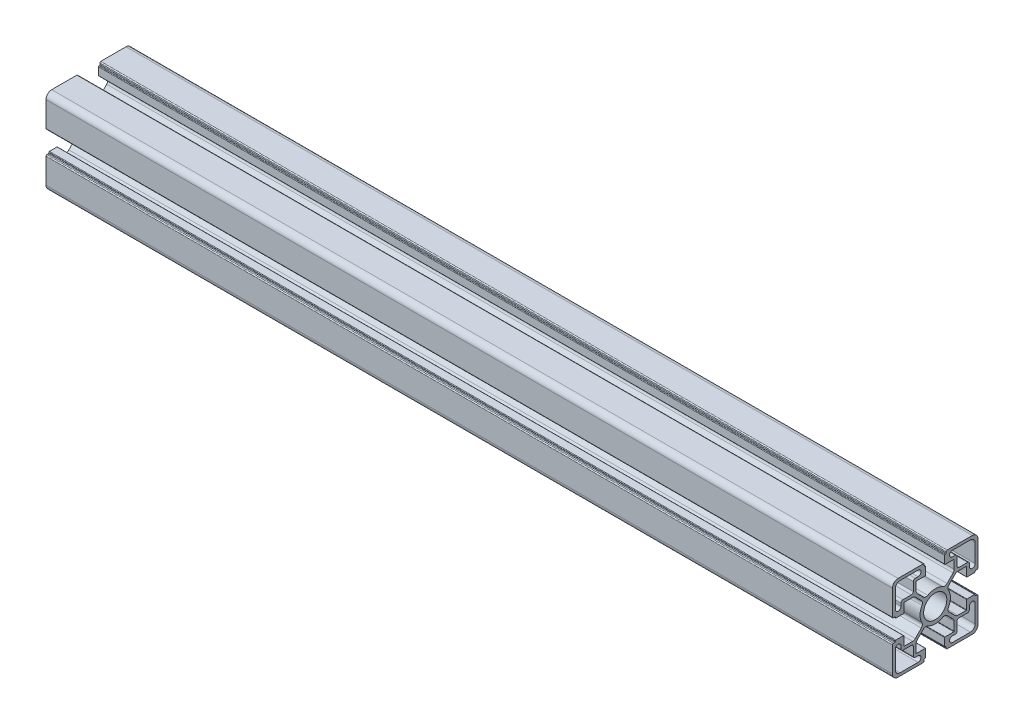
SolidWorks part; units mm, degrees
material "Alliage 6061"
ref_plane "Plan de face" through (0, 0, 0) normal (0, 0, 1) x (1, 0, 0)
ref_plane "Plan de dessus" through (0, 0, 0) normal (0, 1, 0) x (1, 0, 0)
ref_plane "Plan de droite" through (0, 0, 0) normal (1, 0, 0) x (0, 0, -1)
sketch "Esquisse1" plane through (0, 0, 0) normal (1, 0, 0) x (0, 0, -1)
  line L0 (0, 0) -> (-37.5261, 37.5261) construction
  line L1 (0, 0) -> (-46.9556, 0) construction
  line L2 (-22.5, 19.5) -> (-22.5, 6.3)
  line L3 (-20.7, 5) -> (-16.7, 5)
  line L4 (-16.5, 5.2) -> (-16.5, 9.8)
  line L5 (-16.3, 10) -> (-11.8642, 10)
  line L6 (-10.4924, 9.4318) -> (-7.2967, 6.236)
  line L7 (-21, 18.5) -> (-21, 9)
  line L8 (-16.5, 5) -> (-16.5, 10) construction
  line L9 (-18, 9) -> (-18, 10.5)
  line L10 (-17, 11.5) -> (-12.5, 11.5)
  line L11 (-22, 5.8) -> (-21.3, 5.8)
  line L12 (-21, 5.5) -> (-21, 5.3)
  line L13 (-21, 22.5) -> (-21, 6.5) construction
  line L14 (-18, 11.5) -> (-10.4393, 11.5) construction
  line L15 (-10.4393, 11.5) -> (-5.1016, 6.1623) construction
  line L16 (-18, 6.5) -> (-18, 11.5) construction
  line L17 (-22.5, 22.5) -> (-22.5, 5) construction
  line L18 (-22.5, 5) -> (-16.5, 5) construction
  line L19 (-21, 6.5) -> (-18, 6.5) construction
  line L20 (-16.5, 10) -> (-11.0607, 10) construction
  line L21 (-11.0607, 10) -> (-6.1623, 5.1016) construction
  line L22 (-5.5, 21) -> (-5.3, 21)
  line L23 (-5.8, 22) -> (-5.8, 21.3)
  line L24 (-11.5, 17) -> (-11.5, 12.5)
  line L25 (-9, 18) -> (-10.5, 18)
  line L26 (-18.5, 21) -> (-9, 21)
  line L27 (-9.4318, 10.4924) -> (-6.236, 7.2967)
  line L28 (-10, 16.3) -> (-10, 11.8642)
  line L29 (-5.2, 16.5) -> (-9.8, 16.5)
  line L30 (-5, 20.7) -> (-5, 16.7)
  line L31 (-19.5, 22.5) -> (-6.3, 22.5)
  line L32 (19.5, 22.5) -> (6.3, 22.5)
  line L33 (5, 20.7) -> (5, 16.7)
  line L34 (5.2, 16.5) -> (9.8, 16.5)
  line L35 (10, 16.3) -> (10, 11.8642)
  line L36 (9.4318, 10.4924) -> (6.236, 7.2967)
  line L37 (18.5, 21) -> (9, 21)
  line L38 (9, 18) -> (10.5, 18)
  line L39 (11.5, 17) -> (11.5, 12.5)
  line L40 (5.8, 22) -> (5.8, 21.3)
  line L41 (5.5, 21) -> (5.3, 21)
  line L42 (21, 5.5) -> (21, 5.3)
  line L43 (22, 5.8) -> (21.3, 5.8)
  line L44 (17, 11.5) -> (12.5, 11.5)
  line L45 (18, 9) -> (18, 10.5)
  line L46 (21, 18.5) -> (21, 9)
  line L47 (10.4924, 9.4318) -> (7.2967, 6.236)
  line L48 (16.3, 10) -> (11.8642, 10)
  line L49 (16.5, 5.2) -> (16.5, 9.8)
  line L50 (20.7, 5) -> (16.7, 5)
  line L51 (22.5, 19.5) -> (22.5, 6.3)
  line L52 (0, 0) -> (37.5261, 37.5261) construction
  line L53 (0, 0) -> (0, 46.9556) construction
  line L54 (22.5, -19.5) -> (22.5, -6.3)
  line L55 (20.7, -5) -> (16.7, -5)
  line L56 (16.5, -5.2) -> (16.5, -9.8)
  line L57 (16.3, -10) -> (11.8642, -10)
  line L58 (10.4924, -9.4318) -> (7.2967, -6.236)
  line L59 (21, -18.5) -> (21, -9)
  line L60 (18, -9) -> (18, -10.5)
  line L61 (17, -11.5) -> (12.5, -11.5)
  line L62 (22, -5.8) -> (21.3, -5.8)
  line L63 (21, -5.5) -> (21, -5.3)
  line L64 (5.5, -21) -> (5.3, -21)
  line L65 (5.8, -22) -> (5.8, -21.3)
  line L66 (11.5, -17) -> (11.5, -12.5)
  line L67 (9, -18) -> (10.5, -18)
  line L68 (18.5, -21) -> (9, -21)
  line L69 (9.4318, -10.4924) -> (6.236, -7.2967)
  line L70 (10, -16.3) -> (10, -11.8642)
  line L71 (5.2, -16.5) -> (9.8, -16.5)
  line L72 (5, -20.7) -> (5, -16.7)
  line L73 (19.5, -22.5) -> (6.3, -22.5)
  line L74 (0, 0) -> (37.5261, -37.5261) construction
  line L75 (0, 0) -> (46.9556, 0) construction
  line L76 (-19.5, -22.5) -> (-6.3, -22.5)
  line L77 (-5, -20.7) -> (-5, -16.7)
  line L78 (-5.2, -16.5) -> (-9.8, -16.5)
  line L79 (-10, -16.3) -> (-10, -11.8642)
  line L80 (-9.4318, -10.4924) -> (-6.236, -7.2967)
  line L81 (-18.5, -21) -> (-9, -21)
  line L82 (-9, -18) -> (-10.5, -18)
  line L83 (-11.5, -17) -> (-11.5, -12.5)
  line L84 (-5.8, -22) -> (-5.8, -21.3)
  line L85 (-5.5, -21) -> (-5.3, -21)
  line L86 (-21, -5.5) -> (-21, -5.3)
  line L87 (-22, -5.8) -> (-21.3, -5.8)
  line L88 (-17, -11.5) -> (-12.5, -11.5)
  line L89 (-18, -9) -> (-18, -10.5)
  line L90 (-21, -18.5) -> (-21, -9)
  line L91 (-10.4924, -9.4318) -> (-7.2967, -6.236)
  line L92 (-16.3, -10) -> (-11.8642, -10)
  line L93 (-16.5, -5.2) -> (-16.5, -9.8)
  line L94 (-20.7, -5) -> (-16.7, -5)
  line L95 (-22.5, -19.5) -> (-22.5, -6.3)
  line L96 (0, 0) -> (-37.5261, -37.5261) construction
  line L97 (0, 0) -> (0, -46.9556) construction
  arc A0 (0, 6.1) -> (-6.1, 0) centre (0, 0) ccw
  arc A1 (-6.9766, 3.9149) -> (-8, 0) centre (0, 0) ccw
  arc A2 (-21, 9) -> (-18, 9) centre (-19.5, 9) ccw
  arc A3 (-22, 5.8) -> (-22.5, 6.3) centre (-22, 6.3) cw
  arc A4 (-21, 5.3) -> (-20.7, 5) centre (-20.7, 5.3) ccw
  arc A5 (-21.3, 5.8) -> (-21, 5.5) centre (-21.3, 5.5) cw
  arc A6 (-16.5, 9.8) -> (-16.3, 10) centre (-16.3, 9.8) cw
  arc A7 (-16.7, 5) -> (-16.5, 5.2) centre (-16.7, 5.2) ccw
  arc A8 (-7.2967, 6.236) -> (-6.9766, 3.9149) centre (-8.6685, 4.8643) cw
  arc A9 (-11.8642, 10) -> (-10.4924, 9.4318) centre (-11.8642, 8.06) cw
  arc A10 (-18, 10.5) -> (-17, 11.5) centre (-17, 10.5) cw
  arc A11 (-10.5, 18) -> (-11.5, 17) centre (-10.5, 17) ccw
  arc A12 (-10, 11.8642) -> (-9.4318, 10.4924) centre (-8.06, 11.8642) ccw
  arc A13 (-6.236, 7.2967) -> (-3.9149, 6.9766) centre (-4.8643, 8.6685) ccw
  arc A14 (-5, 16.7) -> (-5.2, 16.5) centre (-5.2, 16.7) cw
  arc A15 (-9.8, 16.5) -> (-10, 16.3) centre (-9.8, 16.3) ccw
  arc A16 (-5.8, 21.3) -> (-5.5, 21) centre (-5.5, 21.3) ccw
  arc A17 (-5.3, 21) -> (-5, 20.7) centre (-5.3, 20.7) cw
  arc A18 (-5.8, 22) -> (-6.3, 22.5) centre (-6.3, 22) ccw
  arc A19 (-9, 21) -> (-9, 18) centre (-9, 19.5) cw
  arc A20 (-3.9149, 6.9766) -> (0, 8) centre (0, 0) cw
  arc A21 (-12.5, 11.5) -> (-11.5, 12.5) centre (-12.5, 12.5) ccw
  arc A22 (-21, 18.5) -> (-18.5, 21) centre (-18.5, 18.5) cw
  arc A23 (-22.5, 19.5) -> (-19.5, 22.5) centre (-19.5, 19.5) cw
  arc A24 (6.1, 0) -> (0, 6.1) centre (0, 0) ccw
  arc A25 (3.9149, 6.9766) -> (0, 8) centre (0, 0) ccw
  arc A26 (9, 21) -> (9, 18) centre (9, 19.5) ccw
  arc A27 (5.8, 22) -> (6.3, 22.5) centre (6.3, 22) cw
  arc A28 (5.3, 21) -> (5, 20.7) centre (5.3, 20.7) ccw
  arc A29 (5.8, 21.3) -> (5.5, 21) centre (5.5, 21.3) cw
  arc A30 (9.8, 16.5) -> (10, 16.3) centre (9.8, 16.3) cw
  arc A31 (5, 16.7) -> (5.2, 16.5) centre (5.2, 16.7) ccw
  arc A32 (6.236, 7.2967) -> (3.9149, 6.9766) centre (4.8643, 8.6685) cw
  arc A33 (10, 11.8642) -> (9.4318, 10.4924) centre (8.06, 11.8642) cw
  arc A34 (10.5, 18) -> (11.5, 17) centre (10.5, 17) cw
  arc A35 (18, 10.5) -> (17, 11.5) centre (17, 10.5) ccw
  arc A36 (11.8642, 10) -> (10.4924, 9.4318) centre (11.8642, 8.06) ccw
  arc A37 (7.2967, 6.236) -> (6.9766, 3.9149) centre (8.6685, 4.8643) ccw
  arc A38 (16.7, 5) -> (16.5, 5.2) centre (16.7, 5.2) cw
  arc A39 (16.5, 9.8) -> (16.3, 10) centre (16.3, 9.8) ccw
  arc A40 (21.3, 5.8) -> (21, 5.5) centre (21.3, 5.5) ccw
  arc A41 (21, 5.3) -> (20.7, 5) centre (20.7, 5.3) cw
  arc A42 (22, 5.8) -> (22.5, 6.3) centre (22, 6.3) ccw
  arc A43 (21, 9) -> (18, 9) centre (19.5, 9) cw
  arc A44 (6.9766, 3.9149) -> (8, 0) centre (0, 0) cw
  arc A45 (11.5, 12.5) -> (12.5, 11.5) centre (12.5, 12.5) ccw
  arc A46 (18.5, 21) -> (21, 18.5) centre (18.5, 18.5) cw
  arc A47 (19.5, 22.5) -> (22.5, 19.5) centre (19.5, 19.5) cw
  arc A48 (0, -6.1) -> (6.1, 0) centre (0, 0) ccw
  arc A49 (6.9766, -3.9149) -> (8, 0) centre (0, 0) ccw
  arc A50 (21, -9) -> (18, -9) centre (19.5, -9) ccw
  arc A51 (22, -5.8) -> (22.5, -6.3) centre (22, -6.3) cw
  arc A52 (21, -5.3) -> (20.7, -5) centre (20.7, -5.3) ccw
  arc A53 (21.3, -5.8) -> (21, -5.5) centre (21.3, -5.5) cw
  arc A54 (16.5, -9.8) -> (16.3, -10) centre (16.3, -9.8) cw
  arc A55 (16.7, -5) -> (16.5, -5.2) centre (16.7, -5.2) ccw
  arc A56 (7.2967, -6.236) -> (6.9766, -3.9149) centre (8.6685, -4.8643) cw
  arc A57 (11.8642, -10) -> (10.4924, -9.4318) centre (11.8642, -8.06) cw
  arc A58 (18, -10.5) -> (17, -11.5) centre (17, -10.5) cw
  arc A59 (10.5, -18) -> (11.5, -17) centre (10.5, -17) ccw
  arc A60 (10, -11.8642) -> (9.4318, -10.4924) centre (8.06, -11.8642) ccw
  arc A61 (6.236, -7.2967) -> (3.9149, -6.9766) centre (4.8643, -8.6685) ccw
  arc A62 (5, -16.7) -> (5.2, -16.5) centre (5.2, -16.7) cw
  arc A63 (9.8, -16.5) -> (10, -16.3) centre (9.8, -16.3) ccw
  arc A64 (5.8, -21.3) -> (5.5, -21) centre (5.5, -21.3) ccw
  arc A65 (5.3, -21) -> (5, -20.7) centre (5.3, -20.7) cw
  arc A66 (5.8, -22) -> (6.3, -22.5) centre (6.3, -22) ccw
  arc A67 (9, -21) -> (9, -18) centre (9, -19.5) cw
  arc A68 (3.9149, -6.9766) -> (0, -8) centre (0, 0) cw
  arc A69 (12.5, -11.5) -> (11.5, -12.5) centre (12.5, -12.5) ccw
  arc A70 (21, -18.5) -> (18.5, -21) centre (18.5, -18.5) cw
  arc A71 (22.5, -19.5) -> (19.5, -22.5) centre (19.5, -19.5) cw
  arc A72 (-6.1, 0) -> (0, -6.1) centre (0, 0) ccw
  arc A73 (-3.9149, -6.9766) -> (0, -8) centre (0, 0) ccw
  arc A74 (-9, -21) -> (-9, -18) centre (-9, -19.5) ccw
  arc A75 (-5.8, -22) -> (-6.3, -22.5) centre (-6.3, -22) cw
  arc A76 (-5.3, -21) -> (-5, -20.7) centre (-5.3, -20.7) ccw
  arc A77 (-5.8, -21.3) -> (-5.5, -21) centre (-5.5, -21.3) cw
  arc A78 (-9.8, -16.5) -> (-10, -16.3) centre (-9.8, -16.3) cw
  arc A79 (-5, -16.7) -> (-5.2, -16.5) centre (-5.2, -16.7) ccw
  arc A80 (-6.236, -7.2967) -> (-3.9149, -6.9766) centre (-4.8643, -8.6685) cw
  arc A81 (-10, -11.8642) -> (-9.4318, -10.4924) centre (-8.06, -11.8642) cw
  arc A82 (-10.5, -18) -> (-11.5, -17) centre (-10.5, -17) cw
  arc A83 (-18, -10.5) -> (-17, -11.5) centre (-17, -10.5) ccw
  arc A84 (-11.8642, -10) -> (-10.4924, -9.4318) centre (-11.8642, -8.06) ccw
  arc A85 (-7.2967, -6.236) -> (-6.9766, -3.9149) centre (-8.6685, -4.8643) ccw
  arc A86 (-16.7, -5) -> (-16.5, -5.2) centre (-16.7, -5.2) cw
  arc A87 (-16.5, -9.8) -> (-16.3, -10) centre (-16.3, -9.8) ccw
  arc A88 (-21.3, -5.8) -> (-21, -5.5) centre (-21.3, -5.5) ccw
  arc A89 (-21, -5.3) -> (-20.7, -5) centre (-20.7, -5.3) cw
  arc A90 (-22, -5.8) -> (-22.5, -6.3) centre (-22, -6.3) ccw
  arc A91 (-21, -9) -> (-18, -9) centre (-19.5, -9) cw
  arc A92 (-6.9766, -3.9149) -> (-8, 0) centre (0, 0) cw
  arc A93 (-11.5, -12.5) -> (-12.5, -11.5) centre (-12.5, -12.5) ccw
  arc A94 (-18.5, -21) -> (-21, -18.5) centre (-18.5, -18.5) cw
  arc A95 (-19.5, -22.5) -> (-22.5, -19.5) centre (-19.5, -19.5) cw
  point P78 (-11.5, 11.5)
  point P81 (-21, 21)
  point P295 (0, 0)
  dimension "D1" = 12.2
  dimension "D2" = 16
  dimension "D13" = 0.5
  dimension "D14" = 0.3
  dimension "D15" = 0.2
  dimension "D16" = 1.94
  dimension "D17" = 1
  dimension "D18" = 1
  dimension "D19" = 2.5
  dimension "D4" = 3
  dimension "D3" = 45
  dimension "D5" = 6
  dimension "D6" = 5
  dimension "D7" = 10
  dimension "D8" = 1.5
  dimension "D10" = 0.8
  dimension "D11" = 1.5
  dimension "D12" = 4
  dimension "D9" = 1.5
  dimension "D20" = 4
extrude "Boss.-Extru.1" add sketch "Esquisse1" along normal mid plane 445 contours A95 L76 A75 L84 A77 L85 A76 L77 A79 L78 A78 L79 A81 L80 A80 A73 A68 A61 L69 A60 L70 A63 L71 A62 L72 A65 L64 A64 L65 A66 L73 A71 L54 A51 L62 A53 L63 A52 L55 A55 L56 A54 L57 A57 L58 A56 A49 A44 A37 L47 A36
